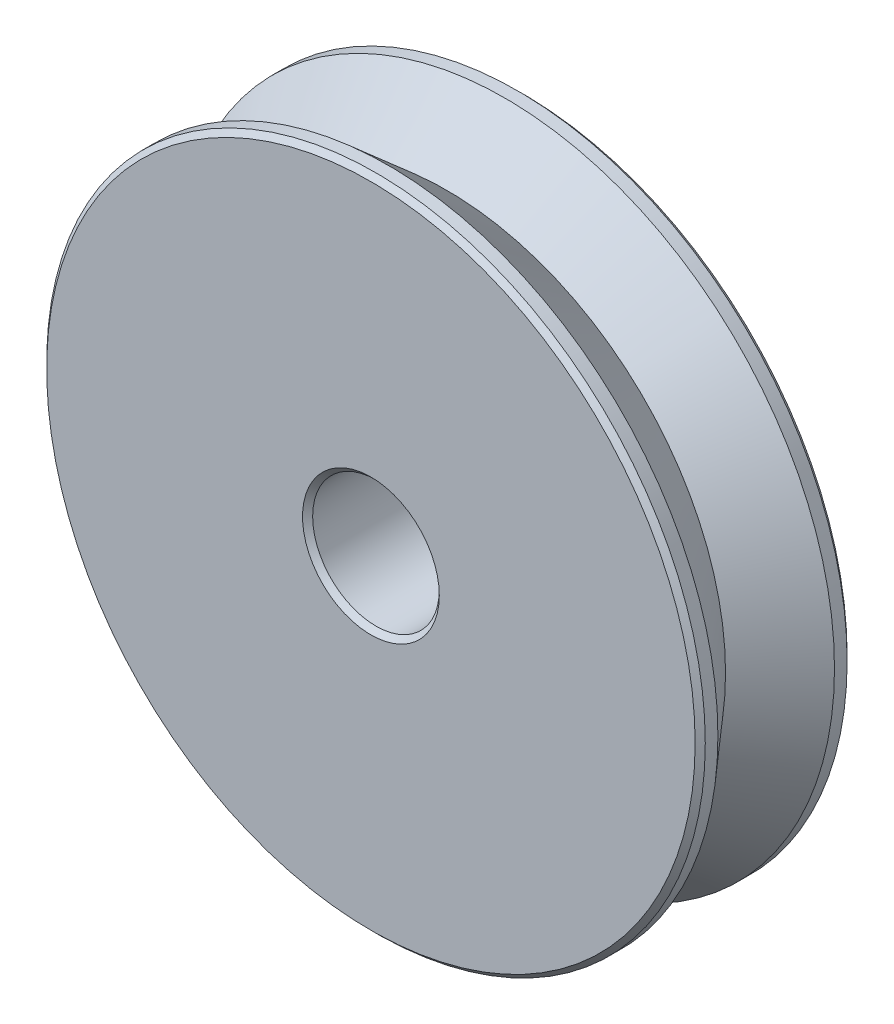
SolidWorks part; units mm, degrees
ref_plane "前视基准面" through (0, 0, 0) normal (0, 0, 1) x (1, 0, 0)
ref_plane "上视基准面" through (0, 0, 0) normal (0, 1, 0) x (1, 0, 0)
ref_plane "右视基准面" through (0, 0, 0) normal (1, 0, 0) x (0, 0, -1)
other "Configuration Table"
sketch "草图1" plane through (0, 0, 0) normal (0, 0, 1) x (1, 0, 0)
  line L0 (0, 0) -> (15.4538, 0) construction
  line L1 (0, 0) -> (0, 17.5112) construction
  circle A0 centre (0, 0) radius 13
  circle A1 centre (0, 0) radius 2.5
  dimension "D1" = 26
  dimension "D2" = 5
extrude "凸台-拉伸1" add sketch "草图1" along normal mid plane 6
sketch "草图2" plane through (0, 0, 0) normal (1, 0, 0) x (0, 0, -1)
  line L0 (0, 0) -> (9.2223, 0) construction
  line L1 (0, 0) -> (0, 13) construction
  line L2 (0, 11) -> (2.3011, 13)
  line L3 (2.3011, 13) -> (-2.3011, 13)
  line L4 (0, 11) -> (-2.3011, 13)
  point P2 (0, 11)
  point P9 (2.2971, 12.9965)
  point P11 (0, 13)
  dimension "D1" = 11
  dimension "D2" = 49.005
  dimension "D3" = 2
revolve "切除-旋转1" cut sketch "草图2" angle 360 about L0
chamfer "倒角1" distance 0.2 angle 45 4 edges at (2.5, 0, -3) (2.5, 0, 3) (13, 0, -3) (13, 0, 3)
